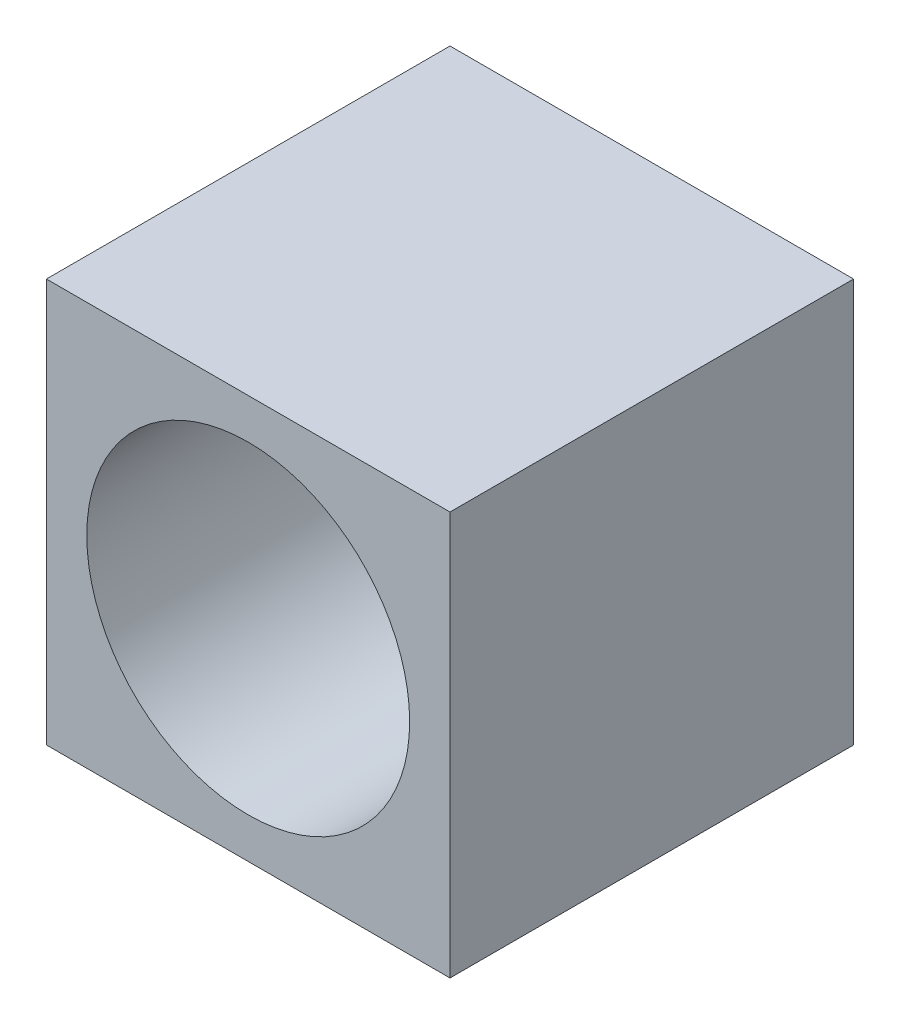
SolidWorks part; units mm, degrees
ref_plane "Alzado" through (0, 0, 0) normal (0, 0, 1) x (1, 0, 0)
ref_plane "Planta" through (0, 0, 0) normal (0, 1, 0) x (1, 0, 0)
ref_plane "Vista lateral" through (0, 0, 0) normal (1, 0, 0) x (0, 0, -1)
sketch "Croquis2" plane through (0, 0, 0) normal (0, 0, 1) x (1, 0, 0)
  line L1 (-5, 5) -> (5, 5)
  line L2 (-5, 5) -> (-5, -5)
  line L3 (-5, -5) -> (5, -5)
  line L4 (5, 5) -> (5, -5)
  line L5 (-5, 5) -> (5, -5) construction
  line L6 (-5, -5) -> (5, 5) construction
  circle A0 centre (0, 0) radius 4
  point P0 (0, 0)
  dimension "D3" = 8
  dimension "D1" = 10
  dimension "D2" = 10
extrude "Saliente-Extruir1" add sketch "Croquis2" along normal blind 10
